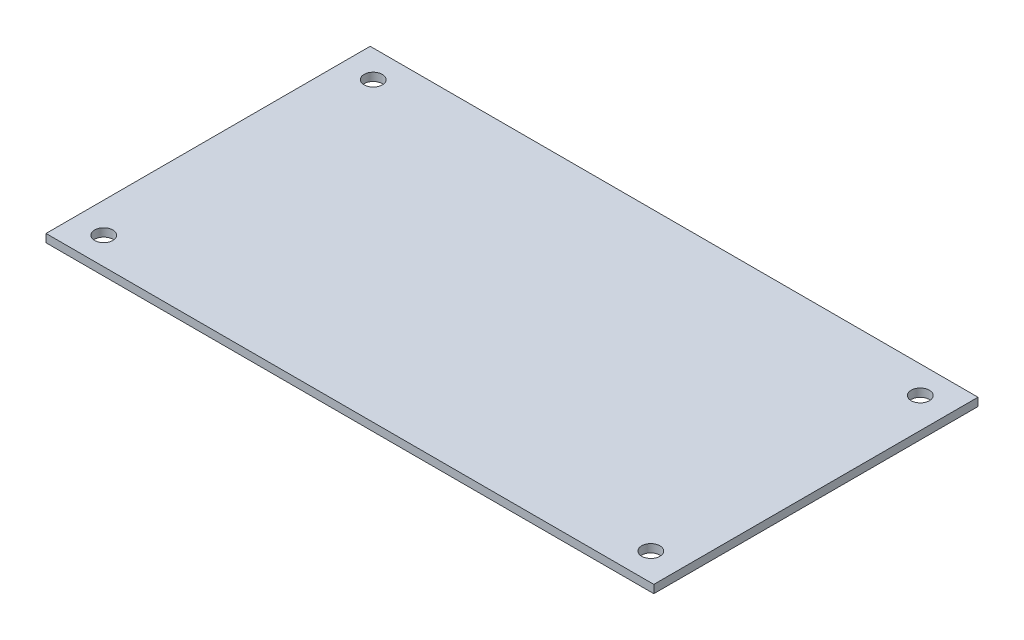
SolidWorks part; units mm, degrees
material "Acrylic (Medium-high impact)"
ref_plane "Front Plane" through (0, 0, 0) normal (0, 0, 1) x (1, 0, 0)
ref_plane "Top Plane" through (0, 0, 0) normal (0, 1, 0) x (1, 0, 0)
ref_plane "Right Plane" through (0, 0, 0) normal (1, 0, 0) x (0, 0, -1)
sketch "Sketch1" plane through (0, 0, 0) normal (0, 1, 0) x (1, 0, 0)
  line L0 (0, 0) -> (300, 0)
  line L1 (300, 0) -> (300, 160)
  line L2 (300, 160) -> (0, 160)
  line L3 (0, 160) -> (0, 0)
extrude "Boss-Extrude2" add sketch "Sketch1" along normal blind 4
sketch "Sketch3" plane through (0, 4, 0) normal (0, 1, 0) x (1, 0, 0)
  line L0 (0, 160) -> (15, 160)
  line L1 (300, 160) -> (0, 160) construction
  line L2 (15, 160) -> (15, 146.5)
  line L3 (15, 146.5) -> (285, 146.5)
  line L4 (285, 146.5) -> (285, 13.5)
  line L5 (285, 13.5) -> (15, 13.5)
  line L6 (15, 13.5) -> (15, 146.5)
  circle A0 centre (15, 146.5) radius 4.5
  circle A1 centre (285, 146.5) radius 4.5
  circle A2 centre (285, 13.5) radius 4.5
  circle A3 centre (15, 13.5) radius 4.5
extrude "Cut-Extrude2" cut sketch "Sketch3" against normal blind 4 contours A0 | A1 | A2 | A3
